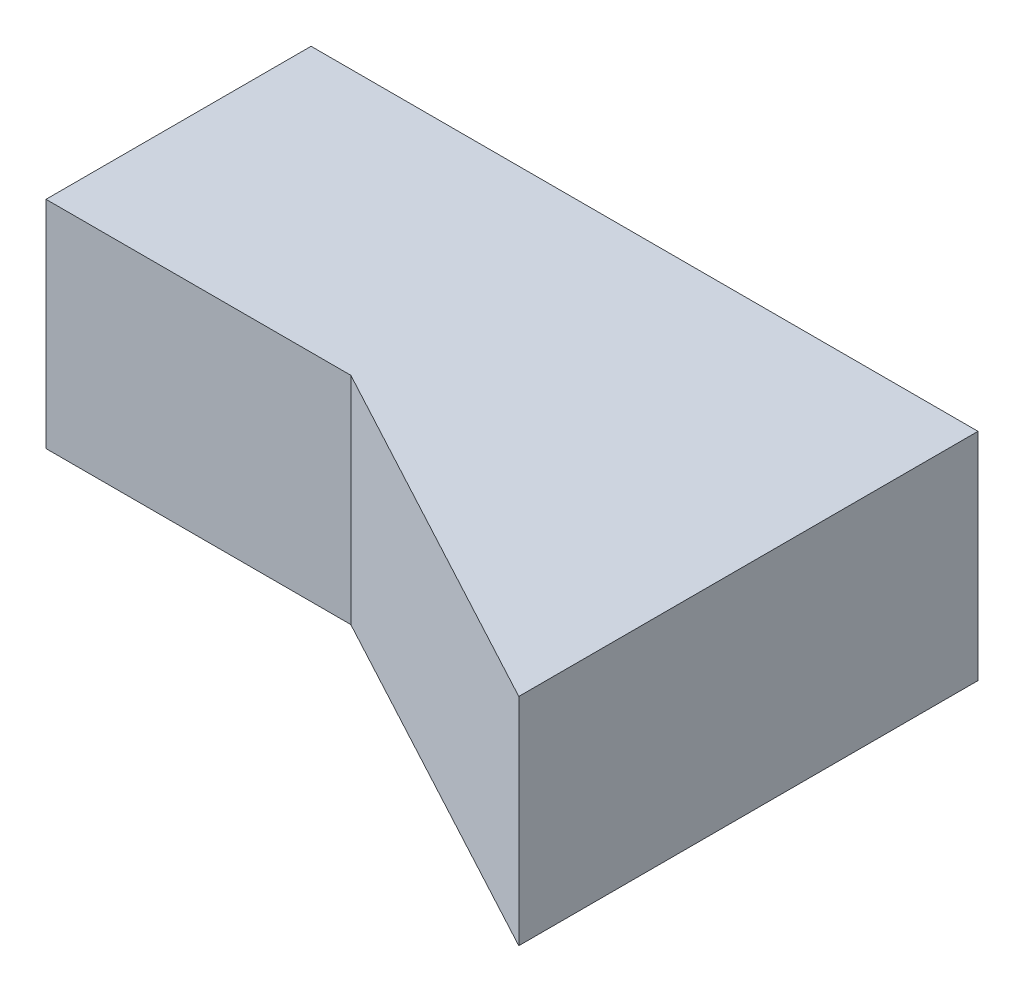
SolidWorks part; units mm, degrees
ref_plane "Front Plane" through (0, 0, 0) normal (0, 0, 1) x (1, 0, 0)
ref_plane "Top Plane" through (0, 0, 0) normal (0, 1, 0) x (1, 0, 0)
ref_plane "Right Plane" through (0, 0, 0) normal (1, 0, 0) x (0, 0, -1)
sketch "Sketch1" plane through (0, 0, 0) normal (0, 1, 0) x (1, 0, 0)
  line L0 (0, 0) -> (-584.2, 0)
  line L1 (0, 0) -> (693.9383, -372.0865)
  line L2 (-584.2, 0) -> (-584.2, 508)
  line L3 (693.9383, -372.0865) -> (693.9383, 508)
  line L4 (-584.2, 508) -> (693.9383, 508)
  dimension "D1" = 584.2
  dimension "D2" = 787.4
  dimension "D3" = 151.8
  dimension "D4" = 508
extrude "Boss-Extrude2" add sketch "Sketch1" along normal blind 413.766
